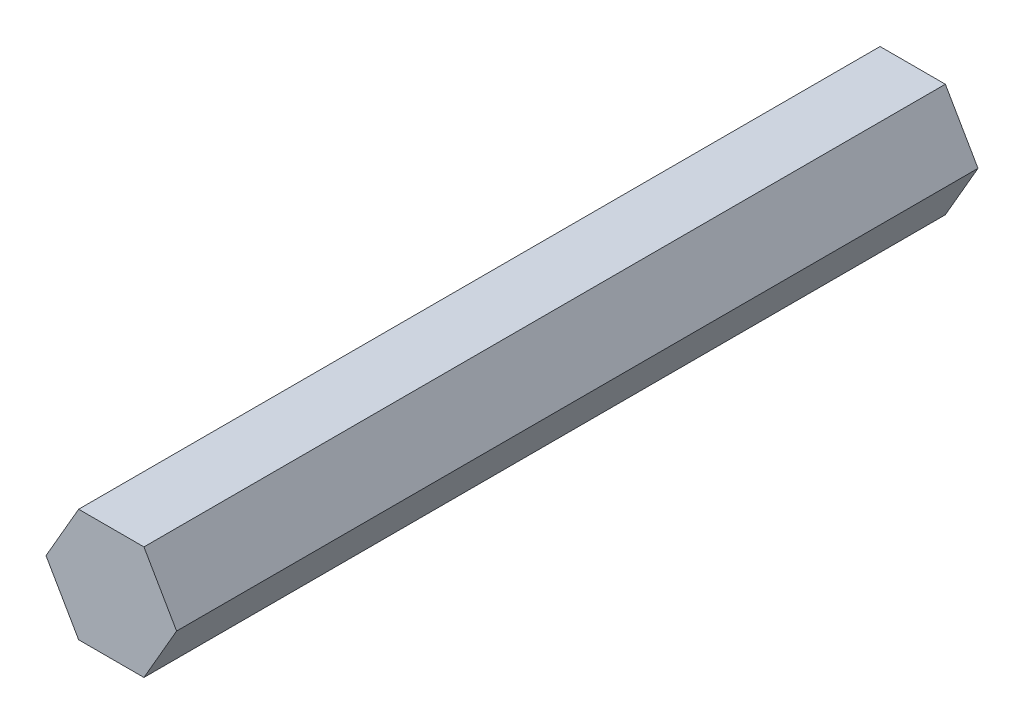
SolidWorks part; units mm, degrees
ref_plane "Front Plane" through (0, 0, 0) normal (0, 0, 1) x (1, 0, 0)
ref_plane "Top Plane" through (0, 0, 0) normal (0, 1, 0) x (1, 0, 0)
ref_plane "Right Plane" through (0, 0, 0) normal (1, 0, 0) x (0, 0, -1)
sketch "Sketch1" plane through (0, 0, 0) normal (0, 0, 1) x (1, 0, 0)
  line L1 (7.3323, 0) -> (3.6662, 6.35)
  line L2 (3.6662, 6.35) -> (-3.6662, 6.35)
  line L3 (-3.6662, 6.35) -> (-7.3323, 0)
  line L4 (-7.3323, 0) -> (-3.6662, -6.35)
  line L5 (-3.6662, -6.35) -> (3.6662, -6.35)
  line L6 (3.6662, -6.35) -> (7.3323, 0)
  circle A0 centre (0, 0) radius 6.35 construction
extrude "Boss-Extrude1" add sketch "Sketch1" along normal blind 90
